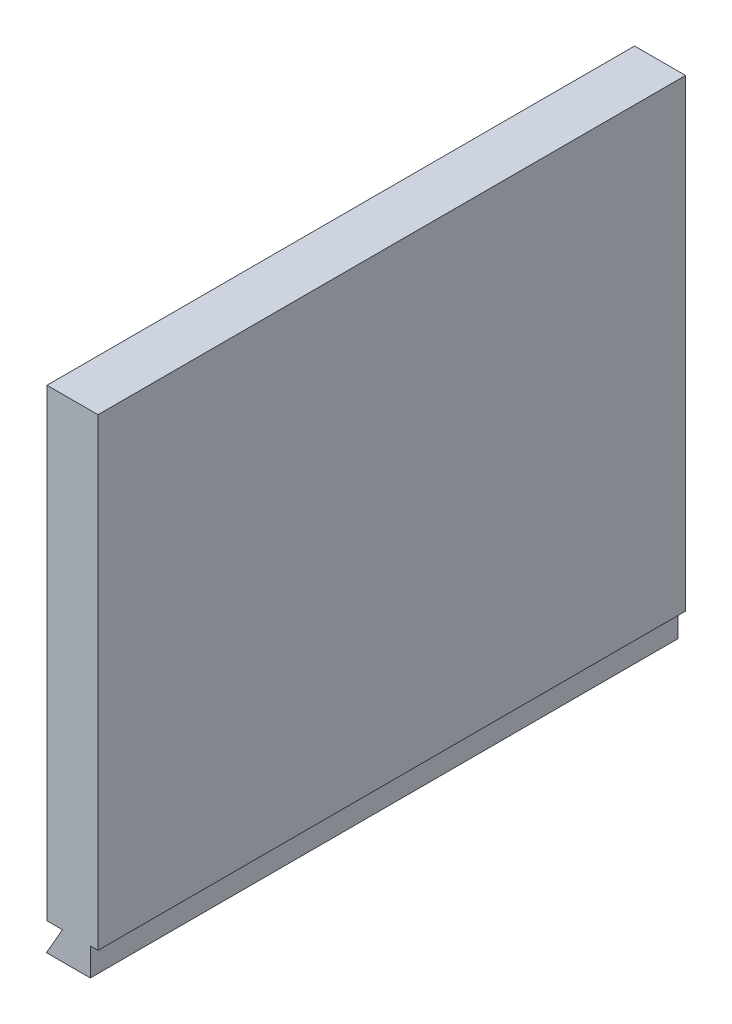
SolidWorks part; units mm, degrees
ref_plane "Front" through (0, 0, 0) normal (0, 0, 1) x (1, 0, 0)
ref_plane "Top" through (0, 0, 0) normal (0, 1, 0) x (1, 0, 0)
ref_plane "Right" through (0, 0, 0) normal (1, 0, 0) x (0, 0, -1)
sketch "Sketch1" plane through (0, 0, 0) normal (0, 0, 1) x (1, 0, 0)
  line L0 (0, 0) -> (-1, 0)
  line L1 (-1, 0) -> (-1, 30)
  line L2 (-1, 30) -> (2.3, 30)
  line L3 (2.3, 30) -> (2.3, 0)
  line L4 (2.3, 0) -> (1.8, 0)
  line L5 (1.8, 0) -> (1.8, -1.8)
  line L6 (1.8, -1.8) -> (-1.0392, -1.8)
  line L7 (-1.0392, -1.8) -> (0, 0)
  dimension "D1" = 1.8
  dimension "D2" = 60
  dimension "D3" = 1.8
  dimension "D4" = 1
  dimension "D5" = 0.5
  dimension "D6" = 30
extrude "Boss-Extrude1" add sketch "Sketch1" along normal blind 38
